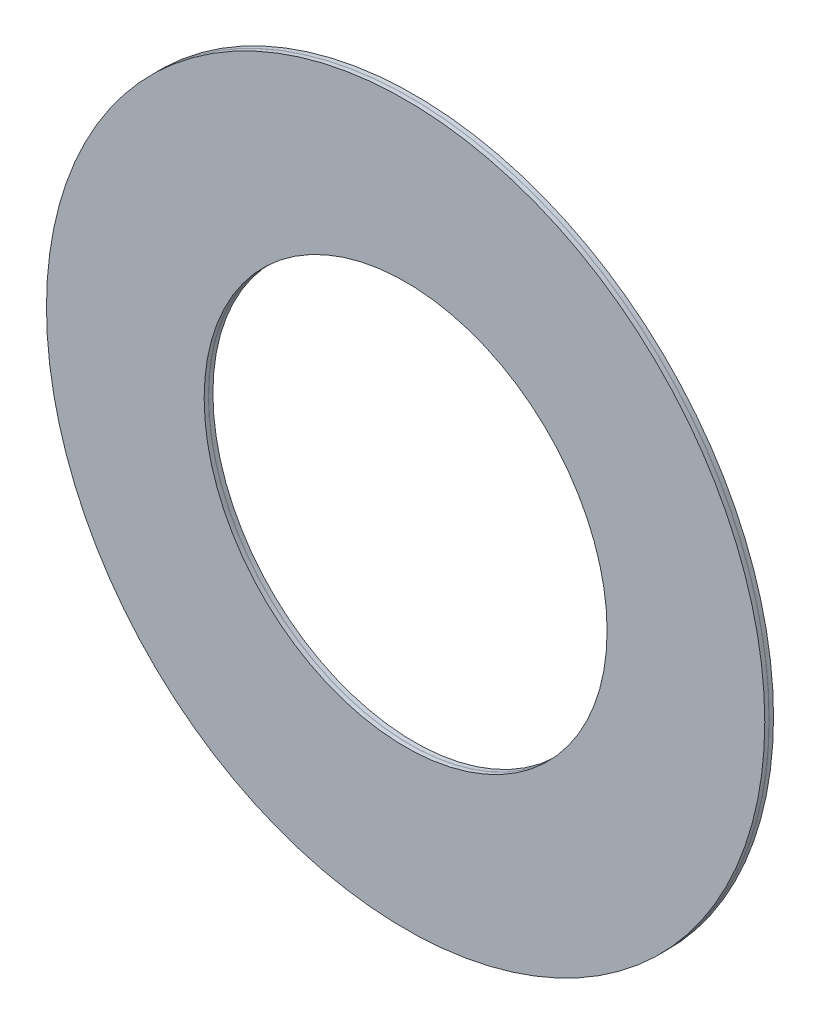
SolidWorks part; units mm, degrees
ref_plane "Front Plane" through (0, 0, 0) normal (0, 0, 1) x (1, 0, 0)
ref_plane "Top Plane" through (0, 0, 0) normal (0, 1, 0) x (1, 0, 0)
ref_plane "Right Plane" through (0, 0, 0) normal (1, 0, 0) x (0, 0, -1)
sketch "Sketch1" plane through (0, 0, 0) normal (0, 0, 1) x (1, 0, 0)
  line L0 (0, 65.0875) -> (0, -65.0875) construction
  line L1 (-65.0875, 0) -> (65.0875, 0) construction
  circle A0 centre (0, 0) radius 65.0875 construction
  circle A1 centre (0, 0) radius 36.5125 construction
  point P8 (0, -36.5125)
  point P9 (36.5125, 0)
  point P10 (0, 36.5125)
  point P11 (-36.5125, 0)
  point P13 (0, 0)
  dimension "D1" = 28.575
  dimension "OD" = 130.175
  dimension "ID" = 73.025
sketch "Sketch2" plane through (0, 0, 0) normal (1, 0, 0) x (0, 0, -1)
  line L0 (0, -65.0875) -> (0, 65.0875) construction
  line L1 (0.7938, 65.0875) -> (-0.7938, 65.0875) construction
  line L2 (0.7938, 65.0875) -> (0.7938, -65.0875) construction
  line L3 (0.7938, -65.0875) -> (-0.7938, -65.0875) construction
  line L4 (-0.7938, 65.0875) -> (-0.7938, -65.0875) construction
  line L5 (0.7938, 0) -> (-0.7938, 0) construction
  line L8 (-0.7937, 36.5125) -> (0.7937, 36.5125) construction
  line L9 (-0.7938, -36.5125) -> (0.7938, -36.5125) construction
  point P8 (0, 0)
  dimension "Thickness" = 1.5875
sketch "Sketch3" plane through (0, 0, 0) normal (1, 0, 0) x (0, 0, -1)
  line L0 (-0.0254, 65.0875) -> (0.0254, 65.0875)
  line L10 (0.7938, 65.0875) -> (-0.7938, 65.0875) construction
  line L11 (-0.0254, 65.0875) -> (-0.0254, 36.5125)
  line L12 (-0.7937, 36.5125) -> (0.7937, 36.5125) construction
  line L13 (-0.0254, 36.5125) -> (0.0254, 36.5125)
  line L16 (0.0254, 36.5125) -> (0.0254, 65.0875)
  point P5 (0, 65.0875)
  dimension "D1" = 0.0508
revolve "Revolve1" add sketch "Sketch3" angle 360 about L5
sketch "Sketch4" plane through (0, 0, 0) normal (1, 0, 0) x (0, 0, -1)
  line L0 (-0.0254, 65.0875) -> (-0.7938, 65.0875)
  line L1 (-0.7938, 65.0875) -> (-0.7937, 36.5125)
  line L2 (-0.7937, 36.5125) -> (-0.0254, 36.5125)
  line L3 (-0.0254, 36.5125) -> (-0.0254, 65.0875)
  line L4 (0.0254, 65.0875) -> (0.7938, 65.0875)
  line L5 (0.7938, 65.0875) -> (0.7937, 36.5125)
  line L6 (0.7937, 36.5125) -> (0.0254, 36.5125)
  line L7 (0.0254, 36.5125) -> (0.0254, 65.0875)
revolve "Revolve2" add sketch "Sketch4" angle 360 about L5
